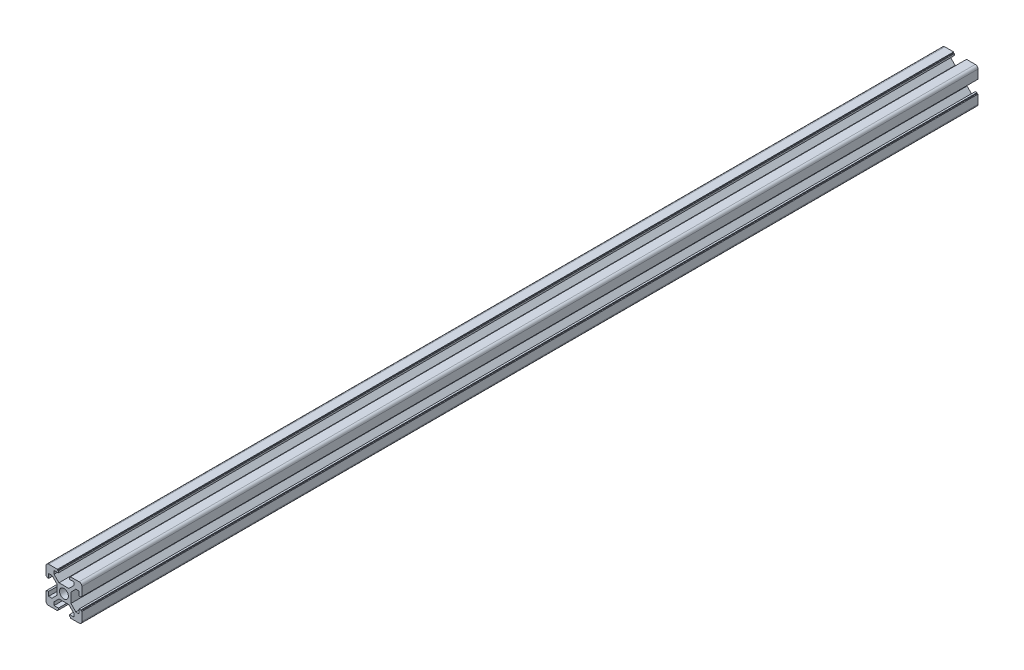
SolidWorks part; units mm, degrees
material "6061 合金"
ref_plane "前视基准面" through (0, 0, 0) normal (0, 0, 1) x (1, 0, 0)
ref_plane "上视基准面" through (0, 0, 0) normal (0, 1, 0) x (1, 0, 0)
ref_plane "右视基准面" through (0, 0, 0) normal (1, 0, 0) x (0, 0, -1)
sketch "草图1" plane through (0, 0, 0) normal (0, 0, 1) x (1, 0, 0)
  line B0 (8.5, 10) -> (3.6, 10)
  line B1 (10, 3.6) -> (10, 8.5)
  line B2 (9.5, 3.6) -> (10, 3.6)
  line B3 (9.5, 3.1) -> (9.5, 3.6)
  line B4 (8.5, 3.1) -> (9.5, 3.1)
  line B5 (8.5, 5.5) -> (8.5, 3.1)
  line B6 (6.65, 5.5) -> (8.5, 5.5)
  line B7 (3.9, 2.75) -> (6.65, 5.5)
  line B8 (3.9, -2.75) -> (3.9, 2.75)
  line B9 (6.65, -5.5) -> (3.9, -2.75)
  line B10 (8.5, -5.5) -> (6.65, -5.5)
  line B11 (8.5, -3.1) -> (8.5, -5.5)
  line B12 (9.5, -3.1) -> (8.5, -3.1)
  line B13 (9.5, -3.6) -> (9.5, -3.1)
  line B14 (10, -3.6) -> (9.5, -3.6)
  line B15 (10, -8.5) -> (10, -3.6)
  line B16 (3.6, -10) -> (8.5, -10)
  line B17 (3.6, -9.5) -> (3.6, -10)
  line B18 (3.1, -9.5) -> (3.6, -9.5)
  line B19 (3.1, -8.5) -> (3.1, -9.5)
  line B20 (5.5, -8.5) -> (3.1, -8.5)
  line B21 (5.5, -6.65) -> (5.5, -8.5)
  line B22 (2.75, -3.9) -> (5.5, -6.65)
  line B23 (-2.75, -3.9) -> (2.75, -3.9)
  line B24 (-5.5, -6.65) -> (-2.75, -3.9)
  line B25 (-5.5, -8.5) -> (-5.5, -6.65)
  line B26 (-3.1, -8.5) -> (-5.5, -8.5)
  line B27 (-3.1, -9.5) -> (-3.1, -8.5)
  line B28 (-3.6, -9.5) -> (-3.1, -9.5)
  line B29 (-3.6, -10) -> (-3.6, -9.5)
  line B30 (-8.5, -10) -> (-3.6, -10)
  line B31 (-10, -3.6) -> (-10, -8.5)
  line B32 (-9.5, -3.6) -> (-10, -3.6)
  line B33 (-9.5, -3.1) -> (-9.5, -3.6)
  line B34 (-8.5, -3.1) -> (-9.5, -3.1)
  line B35 (-8.5, -5.5) -> (-8.5, -3.1)
  line B36 (-6.65, -5.5) -> (-8.5, -5.5)
  line B37 (-3.9, -2.75) -> (-6.65, -5.5)
  line B38 (-3.9, 2.75) -> (-3.9, -2.75)
  line B39 (-6.65, 5.5) -> (-3.9, 2.75)
  line B40 (-8.5, 5.5) -> (-6.65, 5.5)
  line B41 (-8.5, 3.1) -> (-8.5, 5.5)
  line B42 (-9.5, 3.1) -> (-8.5, 3.1)
  line B43 (-9.5, 3.6) -> (-9.5, 3.1)
  line B44 (-10, 3.6) -> (-9.5, 3.6)
  line B45 (-10, 8.5) -> (-10, 3.6)
  line B46 (-3.6, 10) -> (-8.5, 10)
  line B47 (-3.6, 9.5) -> (-3.6, 10)
  line B48 (-3.1, 9.5) -> (-3.6, 9.5)
  line B49 (-3.1, 8.5) -> (-3.1, 9.5)
  line B50 (-5.5, 8.5) -> (-3.1, 8.5)
  line B51 (-5.5, 6.65) -> (-5.5, 8.5)
  line B52 (-2.75, 3.9) -> (-5.5, 6.65)
  line B53 (2.75, 3.9) -> (-2.75, 3.9)
  line B54 (5.5, 6.65) -> (2.75, 3.9)
  line B55 (5.5, 8.5) -> (5.5, 6.65)
  line B56 (3.1, 8.5) -> (5.5, 8.5)
  line B57 (3.1, 9.5) -> (3.1, 8.5)
  line B58 (3.6, 9.5) -> (3.1, 9.5)
  line B59 (3.6, 10) -> (3.6, 9.5)
  arc B60 (-2.5, 0) -> (2.5, 0) centre (0, 0) ccw
  arc B61 (2.5, 0) -> (-2.5, 0) centre (0, 0) ccw
  arc B62 (10, 8.5) -> (8.5, 10) centre (8.5, 8.5) ccw
  arc B63 (8.5, -10) -> (10, -8.5) centre (8.5, -8.5) ccw
  arc B64 (-10, -8.5) -> (-8.5, -10) centre (-8.5, -8.5) ccw
  arc B65 (-8.5, 10) -> (-10, 8.5) centre (-8.5, 8.5) ccw
sketch_block_instance "2020铝型材-1"
sketch_block "2020铝型材"
extrude "凸台-拉伸1" add sketch "草图1" along normal blind 500
sketch "草图2" plane through (0, 3.9, 0) normal (0, 1, 0) x (1, 0, 0)
  line L0 (0, -375) -> (0, -125) construction
  line L1 (2.75, -500) -> (-2.75, -500) construction
  circle A0 centre (0, -250) radius 2.05
  circle A1 centre (0, -125) radius 2.05
  circle A2 centre (0, -375) radius 2.05
  dimension "D1" = 4.1
  dimension "D2" = 4.1
  dimension "D3" = 250
  dimension "D4" = 250
extrude "切除-拉伸1" cut sketch "草图2" against normal through all
sketch "草图3" plane through (10, 0, 0) normal (1, 0, 0) x (0, 0, -1)
  line L0 (-500, -2.75) -> (-500, 2.75) construction
  line L1 (-250, 10) -> (-250, -193.6668) construction
  line L2 (-500, 10) -> (0, 10) construction
  circle A0 centre (-463, 0) radius 2.05
  circle A1 centre (-441, 0) radius 2.05
  circle A2 centre (-59, 0) radius 2.05
  circle A3 centre (-37, 0) radius 2.05
  dimension "D1" = 4.1
  dimension "D2" = 4.1
  dimension "D3" = 22
  dimension "D4" = 37
extrude "切除-拉伸2" cut sketch "草图3" against normal blind 27
